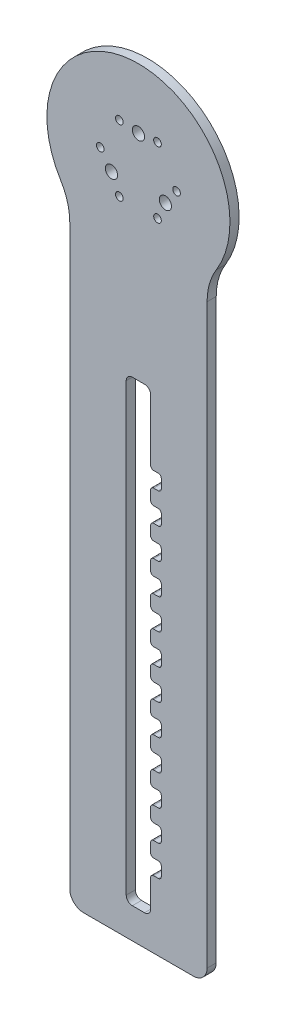
SolidWorks part; units mm, degrees
ref_plane "前视基准面" through (0, 0, 0) normal (0, 0, 1) x (1, 0, 0)
ref_plane "上视基准面" through (0, 0, 0) normal (0, 1, 0) x (1, 0, 0)
ref_plane "右视基准面" through (0, 0, 0) normal (1, 0, 0) x (0, 0, -1)
other "Configuration Table"
sketch "草图1" plane through (0, 0, 0) normal (0, 0, 1) x (1, 0, 0)
  line L0 (0, 100) -> (0, 112.5) construction
  line L1 (-17.9883, -110) -> (17.9883, -110)
  line L2 (-22.5, -105.4883) -> (-22.5, 110) construction
  line L3 (-22.5, 110) -> (22.5, 110) construction
  line L4 (22.5, -105.4883) -> (22.5, 110) construction
  line L5 (-22.5, -110) -> (22.5, 110) construction
  line L6 (-22.5, 110) -> (22.5, -110) construction
  line L7 (0, 110) -> (6.25, 120.8253) construction
  line L8 (0, 110) -> (-6.25, 120.8253) construction
  line L9 (-12.5, 110) -> (0, 110) construction
  line L10 (-6.25, 99.1747) -> (0, 110) construction
  line L11 (6.25, 99.1747) -> (0, 110) construction
  line L12 (0, 110) -> (12.5, 110) construction
  line L13 (0, 110) -> (0, 120.2) construction
  line L14 (0, 110) -> (-8.8335, 104.9) construction
  line L15 (0, 110) -> (8.8335, 104.9) construction
  line L16 (-22.5, -105.4883) -> (-22.5, 83.6609)
  line L17 (22.5, 83.6609) -> (22.5, -105.4883)
  circle A1 centre (0, 110) radius 12.5 construction
  circle A2 centre (12.5, 110) radius 1.25
  circle A3 centre (6.25, 120.8253) radius 1.25
  circle A4 centre (-6.25, 120.8253) radius 1.25
  circle A5 centre (-12.5, 110) radius 1.25
  circle A6 centre (-6.25, 99.1747) radius 1.25
  circle A7 centre (6.25, 99.1747) radius 1.25
  arc A8 (17.9883, -110) -> (22.5, -105.4883) centre (17.9883, -105.4883) ccw
  arc A9 (-17.9883, -110) -> (-22.5, -105.4883) centre (-17.9883, -105.4883) cw
  circle A10 centre (0, 120.2) radius 2
  circle A11 centre (-8.8335, 104.9) radius 2
  circle A12 centre (8.8335, 104.9) radius 2
  arc A13 (25.5, 94.1965) -> (-25.5, 94.1965) centre (0, 110) ccw
  arc A14 (25.5, 94.1965) -> (22.5, 83.6609) centre (42.5, 83.6609) ccw
  arc A15 (-22.5, 83.6609) -> (-25.5, 94.1965) centre (-42.5, 83.6609) ccw
  point P0 (0, 0)
  point P38 (22.5, 90.1569)
  point P41 (-22.5, 90.1569)
  dimension "D3" = 20
  dimension "D4" = 25
  dimension "D12" = 2.5
  dimension "D13" = 2.5
  dimension "D14" = 2.5
  dimension "D15" = 2.5
  dimension "D16" = 2.5
  dimension "D17" = 2.5
  dimension "D18" = 4.5117
  dimension "D20" = 4
  dimension "D21" = 120
  dimension "D23" = 4
  dimension "D26" = 4
  dimension "D27" = 60
  dimension "D1" = 45
  dimension "D2" = 220
  dimension "D5" = 30
  dimension "D6" = 60
  dimension "D7" = 60
  dimension "D8" = 60
  dimension "D9" = 60
  dimension "D10" = 60
  dimension "D11" = 60
  dimension "D19" = 10.2
  dimension "D22" = 10.2
  dimension "D24" = 120
  dimension "D25" = 10.2
extrude "凸台-拉伸1" add sketch "草图1" along normal blind 3
sketch "草图2" plane through (0, 0, 0) normal (0, 0, -1) x (-1, 0, 0)
  circle A0 centre (-6.25, 120.8253) radius 2.5
  circle A1 centre (6.25, 120.8253) radius 2.5
  circle A2 centre (12.5, 110) radius 2.5
  circle A3 centre (6.25, 99.1747) radius 2.5
  circle A4 centre (-6.25, 99.1747) radius 2.5
  circle A5 centre (-12.5, 110) radius 2.5
  dimension "D1" = 5
  dimension "D2" = 5
  dimension "D3" = 5
  dimension "D4" = 5
  dimension "D5" = 5
  dimension "D6" = 5
extrude "切除-拉伸1" cut sketch "草图2" against normal blind 1
sketch "草图3" plane through (0, 0, 0) normal (0, 0, -1) x (-1, 0, 0)
  line L0 (4, -98) -> (22.5, -98) construction
  line L2 (-4, -82) -> (-4, -79)
  line L3 (-2, 50) -> (2, 50)
  line L4 (4, -70) -> (4, 48)
  line L5 (22.5, 83.6609) -> (22.5, -105.4883) construction
  line L6 (2, -100) -> (2, -110) construction
  line L8 (-4, -89) -> (-4, -98)
  line L9 (-2, -100) -> (2, -100)
  line L10 (4, -70) -> (4, -98)
  line L11 (17.9883, -110) -> (-17.9883, -110) construction
  line L13 (-5, -88) -> (-6.5, -88)
  line L14 (-7.5, -87) -> (-7.5, -84)
  line L15 (-6.5, -83) -> (-5, -83)
  line L16 (-5, -78) -> (-6.5, -78)
  line L17 (-7.5, -77) -> (-7.5, -74)
  line L18 (-6.5, -73) -> (-5, -73)
  line L19 (-4, -72) -> (-4, -69)
  line L20 (-5, -68) -> (-6.5, -68)
  line L21 (-7.5, -67) -> (-7.5, -64)
  line L22 (-6.5, -63) -> (-5, -63)
  line L23 (-4, -62) -> (-4, -59)
  line L24 (-5, -58) -> (-6.5, -58)
  line L25 (-7.5, -57) -> (-7.5, -54)
  line L26 (-6.5, -53) -> (-5, -53)
  line L27 (-4, -52) -> (-4, -49)
  line L28 (-5, -48) -> (-6.5, -48)
  line L29 (-7.5, -47) -> (-7.5, -44)
  line L30 (-6.5, -43) -> (-5, -43)
  line L31 (-4, -42) -> (-4, 48) construction
  line L32 (-4, -53) -> (-4, -48) construction
  line L33 (-4, -63) -> (-4, -58) construction
  line L34 (-4, -73) -> (-4, -68) construction
  line L35 (-4, -43) -> (-4, -39)
  line L36 (-5, -38) -> (-6.5, -38)
  line L37 (-7.5, -37) -> (-7.5, -34)
  line L38 (-6.5, -33) -> (-5, -33)
  line L39 (-4, -32) -> (-4, -29)
  line L40 (-5, -28) -> (-6.5, -28)
  line L41 (-7.5, -27) -> (-7.5, -24)
  line L42 (-6.5, -23) -> (-5, -23)
  line L43 (-4, -22) -> (-4, -19)
  line L44 (-5, -18) -> (-6.5, -18)
  line L45 (-7.5, -14) -> (-7.5, -17)
  line L46 (-6.5, -13) -> (-5, -13)
  line L47 (-4, -12) -> (-4, -8)
  line L48 (-4, -13) -> (-4, -9)
  line L49 (-5, -8) -> (-6.5, -8)
  line L50 (-7.5, -7) -> (-7.5, -4)
  line L51 (-6.5, -3) -> (-5, -3)
  line L52 (-4, -2) -> (-4, 1)
  line L53 (-5, 2) -> (-6.5, 2)
  line L54 (-7.5, 3) -> (-7.5, 6)
  line L55 (-6.5, 7) -> (-5, 7)
  line L56 (-4, 8) -> (-4, 11)
  line L57 (-5, 12) -> (-6.5, 12)
  line L58 (-7.5, 13) -> (-7.5, 16)
  line L59 (-6.5, 17) -> (-5, 17)
  line L60 (-4, 18) -> (-4, 21)
  line L61 (-5, 22) -> (-6.5, 22)
  line L62 (-7.5, 23) -> (-7.5, 26)
  line L63 (-6.5, 27) -> (-5, 27)
  line L64 (-4, -3) -> (-4, 2)
  line L65 (-4, -8) -> (-4, -3) construction
  line L66 (-4, 7) -> (-4, 12)
  line L67 (-4, 2) -> (-4, 7) construction
  line L68 (-4, 17) -> (-4, 22)
  line L69 (-4, 12) -> (-4, 17) construction
  line L70 (-4, 28) -> (-4, 48)
  line L71 (-4, 22) -> (-4, 27) construction
  arc A0 (2, 50) -> (4, 48) centre (2, 48) cw
  arc A1 (-4, 48) -> (-2, 50) centre (-2, 48) cw
  arc A2 (2, -100) -> (4, -98) centre (2, -98) ccw
  arc A3 (-4, -98) -> (-2, -100) centre (-2, -98) ccw
  arc A4 (-4, -89) -> (-5, -88) centre (-5, -89) ccw
  arc A5 (-6.5, -88) -> (-7.5, -87) centre (-6.5, -87) cw
  arc A6 (-7.5, -84) -> (-6.5, -83) centre (-6.5, -84) cw
  arc A7 (-4, -82) -> (-5, -83) centre (-5, -82) cw
  arc A8 (-4, -79) -> (-5, -78) centre (-5, -79) ccw
  arc A9 (-6.5, -78) -> (-7.5, -77) centre (-6.5, -77) cw
  arc A10 (-7.5, -74) -> (-6.5, -73) centre (-6.5, -74) cw
  arc A11 (-5, -73) -> (-4, -72) centre (-5, -72) ccw
  arc A12 (-4, -69) -> (-5, -68) centre (-5, -69) ccw
  arc A13 (-6.5, -68) -> (-7.5, -67) centre (-6.5, -67) cw
  arc A14 (-7.5, -64) -> (-6.5, -63) centre (-6.5, -64) cw
  arc A15 (-5, -63) -> (-4, -62) centre (-5, -62) ccw
  arc A16 (-4, -59) -> (-5, -58) centre (-5, -59) ccw
  arc A17 (-6.5, -58) -> (-7.5, -57) centre (-6.5, -57) cw
  arc A18 (-7.5, -54) -> (-6.5, -53) centre (-6.5, -54) cw
  arc A19 (-5, -53) -> (-4, -52) centre (-5, -52) ccw
  arc A20 (-4, -49) -> (-5, -48) centre (-5, -49) ccw
  arc A21 (-6.5, -48) -> (-7.5, -47) centre (-6.5, -47) cw
  arc A22 (-7.5, -44) -> (-6.5, -43) centre (-6.5, -44) cw
  arc A23 (-5, -43) -> (-4, -42) centre (-5, -42) ccw
  arc A24 (-6.5, -38) -> (-7.5, -37) centre (-6.5, -37) cw
  arc A25 (-4, -39) -> (-5, -38) centre (-5, -39) ccw
  arc A26 (-7.5, -34) -> (-6.5, -33) centre (-6.5, -34) cw
  arc A27 (-5, -33) -> (-4, -32) centre (-5, -32) ccw
  arc A28 (-4, -29) -> (-5, -28) centre (-5, -29) ccw
  arc A29 (-6.5, -28) -> (-7.5, -27) centre (-6.5, -27) cw
  arc A30 (-7.5, -24) -> (-6.5, -23) centre (-6.5, -24) cw
  arc A31 (-5, -23) -> (-4, -22) centre (-5, -22) ccw
  arc A32 (-4, -19) -> (-5, -18) centre (-5, -19) ccw
  arc A33 (-6.5, -18) -> (-7.5, -17) centre (-6.5, -17) cw
  arc A34 (-7.5, -14) -> (-6.5, -13) centre (-6.5, -14) cw
  arc A35 (-5, -13) -> (-4, -12) centre (-5, -12) ccw
  arc A36 (-4, -9) -> (-5, -8) centre (-5, -9) ccw
  arc A37 (-6.5, -8) -> (-7.5, -7) centre (-6.5, -7) cw
  arc A38 (-7.5, -4) -> (-6.5, -3) centre (-6.5, -4) cw
  arc A39 (-5, -3) -> (-4, -2) centre (-5, -2) ccw
  arc A40 (-4, 1) -> (-5, 2) centre (-5, 1) ccw
  arc A41 (-6.5, 2) -> (-7.5, 3) centre (-6.5, 3) cw
  arc A42 (-7.5, 6) -> (-6.5, 7) centre (-6.5, 6) cw
  arc A43 (-5, 7) -> (-4, 8) centre (-5, 8) ccw
  arc A44 (-4, 11) -> (-5, 12) centre (-5, 11) ccw
  arc A45 (-6.5, 12) -> (-7.5, 13) centre (-6.5, 13) cw
  arc A46 (-7.5, 16) -> (-6.5, 17) centre (-6.5, 16) cw
  arc A47 (-5, 17) -> (-4, 18) centre (-5, 18) ccw
  arc A48 (-6.5, 22) -> (-7.5, 23) centre (-6.5, 23) cw
  arc A49 (-7.5, 26) -> (-6.5, 27) centre (-6.5, 26) cw
  arc A50 (-4, 21) -> (-5, 22) centre (-5, 21) ccw
  arc A51 (-5, 27) -> (-4, 28) centre (-5, 28) ccw
  point P0 (0, 0)
  point P18 (4, -100)
  point P21 (-4, -100)
  point P46 (-4, -88)
  point P49 (-7.5, -88)
  point P52 (-7.5, -83)
  point P55 (-4, -83)
  point P58 (-4, -78)
  point P61 (-7.5, -78)
  point P64 (-7.5, -73)
  point P73 (-7.5, -68)
  point P76 (-7.5, -63)
  point P85 (-7.5, -58)
  point P88 (-7.5, -53)
  point P97 (-7.5, -48)
  point P100 (-7.5, -43)
  point P103 (-4, -43)
  point P118 (-7.5, -38)
  point P121 (-4, -38)
  point P124 (-7.5, -33)
  point P127 (-4, -33)
  point P130 (-4, -28)
  point P133 (-7.5, -28)
  point P136 (-7.5, -23)
  point P139 (-4, -23)
  point P142 (-4, -18)
  point P145 (-7.5, -18)
  point P148 (-7.5, -13)
  point P151 (-4, -13)
  point P174 (-7.5, -8)
  point P177 (-7.5, -3)
  point P186 (-7.5, 2)
  point P189 (-7.5, 7)
  point P198 (-7.5, 12)
  point P201 (-7.5, 17)
  point P207 (-7.5, 22)
  point P210 (-7.5, 27)
  dimension "D5" = 2
  dimension "D6" = 10
  dimension "D3" = 10
  dimension "D22" = 1
  dimension "D32" = 1
  dimension "D45" = 1
  dimension "D1" = 150
  dimension "D2" = 18.5
  dimension "D4" = 8
  dimension "D7" = 5
  dimension "D8" = 3.5
  dimension "D9" = 3.5
  dimension "D10" = 5
  dimension "D11" = 5
  dimension "D12" = 5
  dimension "D13" = 5
  dimension "D14" = 3.5
  dimension "D15" = 3.5
  dimension "D16" = 5
  dimension "D17" = 5
  dimension "D18" = 3.5
  dimension "D19" = 5
  dimension "D20" = 5
  dimension "D21" = 5
  dimension "D23" = 5
  dimension "D24" = 5
  dimension "D25" = 5
  dimension "D26" = 3.5
  dimension "D27" = 3.5
  dimension "D28" = 5
  dimension "D29" = 5
  dimension "D30" = 5
  dimension "D31" = 3.5
  dimension "D33" = 5
  dimension "D34" = 5
  dimension "D35" = 5
  dimension "D36" = 5
  dimension "D37" = 5
  dimension "D38" = 5
  dimension "D39" = 5
  dimension "D40" = 5
  dimension "D41" = 3.5
  dimension "D42" = 3.5
  dimension "D43" = 3.5
  dimension "D44" = 3.5
extrude "切除-拉伸2" cut sketch "草图3" against normal blind 10
